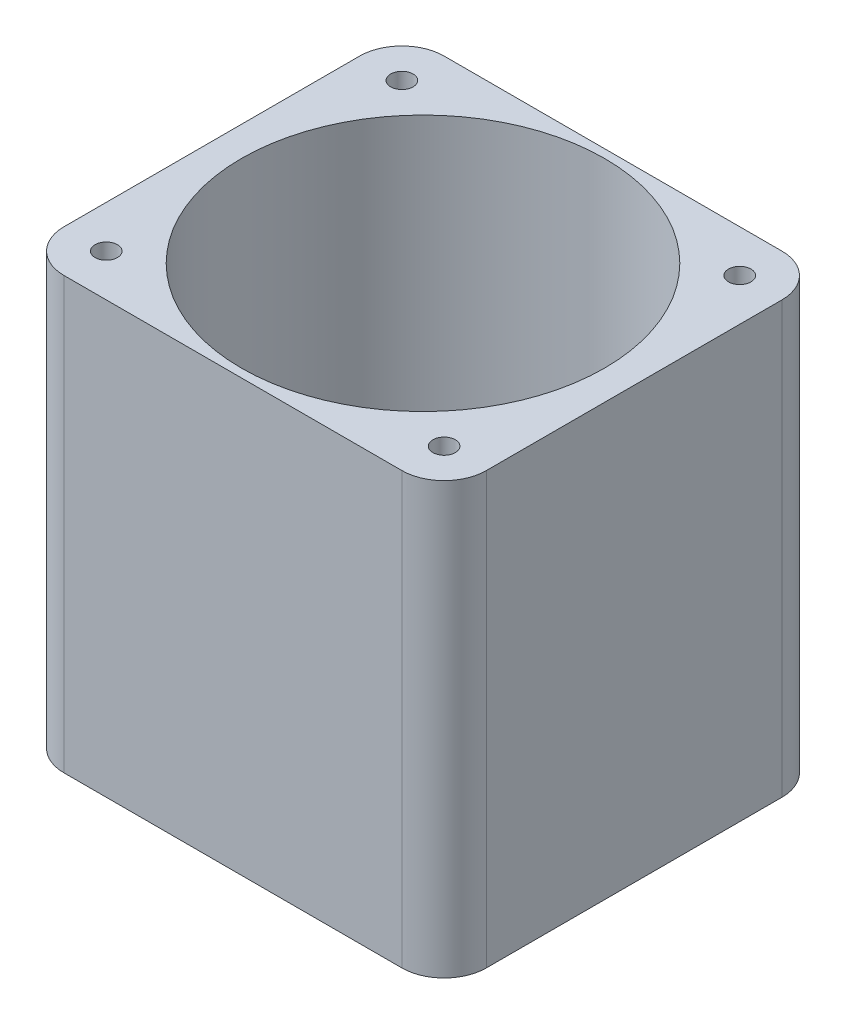
SolidWorks part; units mm, degrees
ref_plane "前视基准面" through (0, 0, 0) normal (0, 0, 1) x (1, 0, 0)
ref_plane "上视基准面" through (0, 0, 0) normal (0, 1, 0) x (1, 0, 0)
ref_plane "右视基准面" through (0, 0, 0) normal (1, 0, 0) x (0, 0, -1)
other "Configuration Table"
sketch "草图1" plane through (0, 0, 0) normal (0, 1, 0) x (1, 0, 0)
  line L0 (0, 45) -> (0, -45) construction
  line L1 (-40, 45) -> (40, 45)
  line L2 (-50, 35) -> (-50, -35)
  line L3 (-40, -45) -> (40, -45)
  line L4 (50, 35) -> (50, -35)
  line L5 (-50, 45) -> (50, -45) construction
  line L6 (-50, -45) -> (50, 45) construction
  line L7 (-50, 0) -> (50, 0) construction
  line L13 (-40, 35) -> (40, -35) construction
  line L14 (-40, -35) -> (40, 35) construction
  circle A0 centre (-40, 35) radius 2.65
  circle A1 centre (40, 35) radius 2.65
  circle A2 centre (40, -35) radius 2.65
  circle A3 centre (-40, -35) radius 2.65
  arc A4 (40, -45) -> (50, -35) centre (40, -35) ccw
  arc A5 (-50, -35) -> (-40, -45) centre (-40, -35) ccw
  arc A6 (40, 45) -> (50, 35) centre (40, 35) cw
  arc A7 (-40, 45) -> (-50, 35) centre (-40, 35) ccw
  point P0 (0, 0)
  point P30 (0, 0)
  dimension "D5" = 5.3
  dimension "D6" = 10
  dimension "D1" = 100
  dimension "D2" = 90
  dimension "D3" = 80
  dimension "D4" = 70
extrude "凸台-拉伸1" add sketch "草图1" along normal blind 102
sketch "草图3" plane through (0, 102, 0) normal (0, 1, 0) x (1, 0, 0)
  line L0 (-50, 0) -> (50, 0) construction
  line L1 (-50, 35) -> (-50, -35) construction
  line L2 (50, -35) -> (50, 35) construction
  line L3 (0, 45) -> (0, -45) construction
  line L4 (40, 45) -> (-40, 45) construction
  line L5 (-40, -45) -> (40, -45) construction
  circle A0 centre (0, 0) radius 43
  point P15 (-0.3692, 0.5539)
  point P16 (-5.6969, 4.3518)
  dimension "D1" = 86
extrude "切除-拉伸1" cut sketch "草图3" against normal through all
